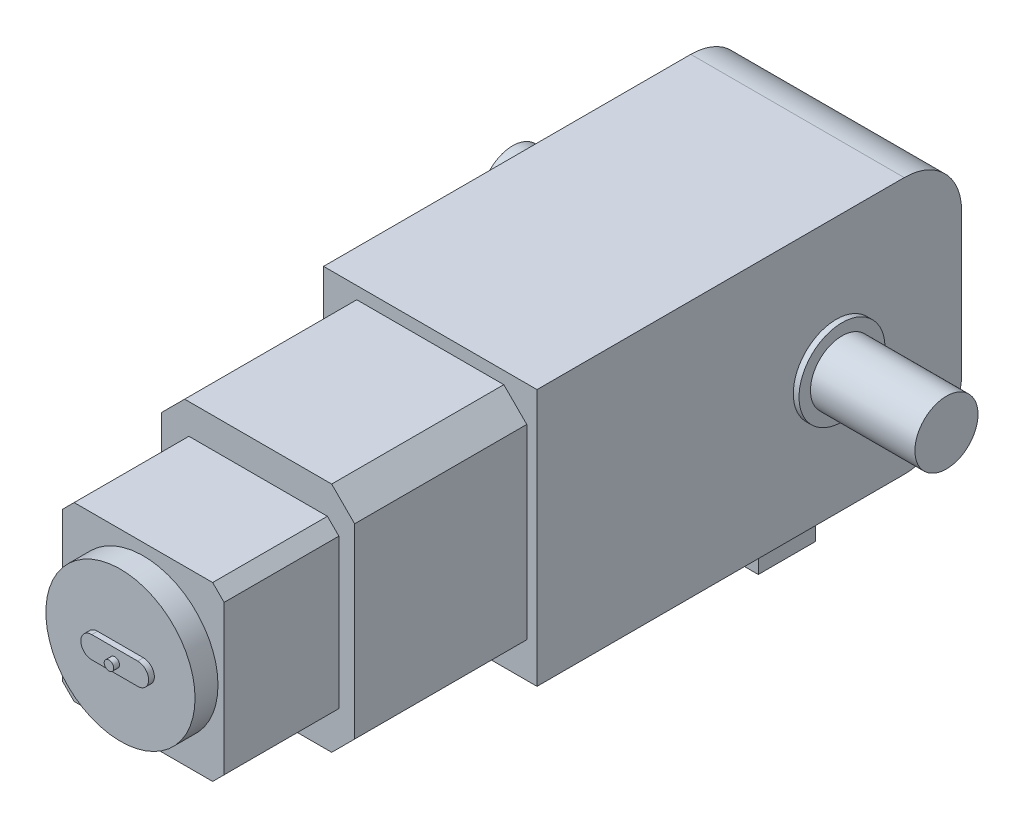
SolidWorks part; units mm, degrees
ref_plane "Front Plane" through (0, 0, 0) normal (0, 0, 1) x (1, 0, 0)
ref_plane "Top Plane" through (0, 0, 0) normal (0, 1, 0) x (1, 0, 0)
ref_plane "Right Plane" through (0, 0, 0) normal (1, 0, 0) x (0, 0, -1)
sketch "Sketch2" plane through (0, 0, 0) normal (1, 0, 0) x (0, 0, -1)
  line L1 (0, 0) -> (32, 0)
  line L2 (0, 0) -> (0, -22.4)
  line L3 (0, -22.4) -> (32, -22.4)
  line L4 (37, -5) -> (37, -17.4)
  arc A0 (32, -22.4) -> (37, -17.4) centre (32, -17.4) ccw
  arc A1 (37, -5) -> (32, 0) centre (32, -5) ccw
  dimension "D1" = 5
extrude "Boss-Extrude2" add sketch "Sketch2" against normal blind 18.6
ref_plane "Plane1" through (-9.3, 0, 0) normal (1, 0, 0) x (0, 0, -1)
sketch "Sketch3" plane through (-9.3, 0, 0) normal (1, 0, 0) x (0, 0, -1)
  line L0 (39, -11.9875) -> (39, -10.9875)
  line L1 (38.5, -10.4875) -> (37, -10.4875)
  line L2 (37, -17.4) -> (37, -5) construction
  line L3 (38.5, -12.4875) -> (37, -12.4875)
  line L4 (37, -17.4) -> (37, -12.4875)
  line L5 (37, -10.4875) -> (37, -12.4875)
  line L8 (0, 0) -> (0, -22.4)
  line L9 (0, -22.4) -> (32, -22.4)
  line L10 (37, -17.4) -> (37, -5)
  line L11 (32, 0) -> (0, 0)
  line L12 (0, 0) -> (0, -22.4)
  line L13 (0, -22.4) -> (32, -22.4)
  line L14 (37, -10.4875) -> (37, -5)
  line L15 (32, 0) -> (0, 0)
  arc A0 (39, -11.9875) -> (38.5, -12.4875) centre (38.5, -11.9875) cw
  arc A1 (39, -10.9875) -> (38.5, -10.4875) centre (38.5, -10.9875) ccw
  arc A4 (32, -22.4) -> (37, -17.4) centre (32, -17.4) ccw
  arc A5 (37, -5) -> (32, 0) centre (32, -5) ccw
  arc A6 (32, -22.4) -> (37, -17.4) centre (32, -17.4) ccw
  arc A7 (37, -5) -> (32, 0) centre (32, -5) ccw
  point P3 (39, -11.4875)
  dimension "D1" = 0.5
  dimension "D2" = 0
extrude "Boss-Extrude3" add sketch "Sketch3" along normal blind 1 and the other way blind 1 contours L0 A1 L1 L5 L3 A0
sketch "Sketch4" plane through (-8.3, 0, 0) normal (1, 0, 0) x (0, 0, -1)
  circle A0 centre (37.8414, -11.4831) radius 0.75
  dimension "2.8" = 1.5
extrude "Cut-Extrude1" cut sketch "Sketch4" against normal through all
sketch "Sketch5" plane through (0, 0, 0) normal (0, 0, 1) x (1, 0, 0)
  line L0 (-17.7069, -3.0755) -> (-15.7069, -1.0755)
  line L1 (0, -22.4) -> (0, 0)
  line L2 (-2.8931, -1.0755) -> (-0.8931, -3.0755)
  line L3 (-17.7069, -19.3245) -> (-15.7069, -21.3245)
  line L4 (-15.7069, -1.0755) -> (-2.8931, -1.0755)
  line L5 (-17.7069, -3.0755) -> (-17.7069, -19.3245)
  line L6 (-15.7069, -21.3245) -> (-2.8931, -21.3245)
  line L7 (-0.8931, -3.0755) -> (-0.8931, -19.3245)
  line L8 (-2.8931, -21.3245) -> (-0.8931, -19.3245)
  point P4 (-9.3, -11.2)
  point P9 (-0.8931, -21.3245)
  point P10 (-17.7069, -1.0755)
  point P11 (-17.7069, -21.3245)
  point P12 (-0.8931, -1.0755)
extrude "Boss-Extrude5" add sketch "Sketch5" along normal blind 15 contours L6 L8 L7 L2 L4 L0 L5 L3
sketch "Sketch6" plane through (0, 0, 15) normal (0, 0, 1) x (1, 0, 0)
  line L0 (-9.3, -12.32) -> (-9.3, 12.32) construction
  line L1 (-15.3351, -3.6927) -> (-3.2649, -3.6927)
  line L2 (-16.3351, -4.6927) -> (-16.3351, -17.7073)
  line L3 (-15.3351, -18.7073) -> (-3.2649, -18.7073)
  line L4 (-2.2649, -4.6927) -> (-2.2649, -17.7073)
  line L5 (-16.3351, -4.6927) -> (-15.3351, -3.6927)
  line L6 (-3.2649, -3.6927) -> (-2.2649, -4.6927)
  line L7 (-3.2649, -18.7073) -> (-2.2649, -17.7073)
  line L8 (-16.3351, -17.7073) -> (-15.3351, -18.7073)
  point P0 (-9.3, -11.2)
  point P1 (-2.2649, -18.7073)
  point P2 (-16.3351, -3.6927)
  point P3 (-16.3351, -18.7073)
  point P4 (-2.2649, -3.6927)
extrude "Boss-Extrude6" add sketch "Sketch6" along normal blind 10
sketch "Sketch7" plane through (0, 0, 25) normal (0, 0, 1) x (1, 0, 0)
  line L0 (-9.3, -12.32) -> (-9.3, 12.32) construction
  circle A0 centre (-9.3, -11.2) radius 6.5
  dimension "D1" = 13
extrude "Boss-Extrude7" add sketch "Sketch7" along normal blind 2
sketch "Sketch8" plane through (0, 0, 27) normal (0, 0, 1) x (1, 0, 0)
  line L0 (-11.3, -10.3878) -> (-7.3, -10.3878)
  line L2 (-11.3, -12.2954) -> (-7.3, -12.2954)
  arc A0 (-11.3, -10.3878) -> (-11.3, -12.2954) centre (-11.3, -11.3416) ccw
  arc A1 (-7.3, -10.3878) -> (-7.3, -12.2954) centre (-7.3, -11.3416) cw
  point P3 (-9.3, -10.3878)
  point P6 (-9.3, -12.2954)
extrude "Boss-Extrude8" add sketch "Sketch8" along normal blind 0.5
sketch "Sketch9" plane through (0, 0, 27.5) normal (0, 0, 1) x (1, 0, 0)
  line L0 (-9.3, -12.32) -> (-9.3, 12.32) construction
  circle A0 centre (-9.3, -11.4732) radius 0.4148
extrude "Boss-Extrude9" add sketch "Sketch9" along normal blind 0.5
sketch "Sketch11" plane through (0, 0, 0) normal (1, 0, 0) x (0, 0, -1)
  circle A1 centre (26.079, -11.4831) radius 3.746
extrude "Boss-Extrude10" add sketch "Sketch11" along normal blind 0.5
sketch "Sketch12" plane through (0.5, 0, 0) normal (1, 0, 0) x (0, 0, -1)
  circle A0 centre (26.079, -11.4831) radius 2.75
  dimension "D1" = 5.5
sketch "Sketch13" plane through (-18.6, 0, 0) normal (-1, 0, 0) x (0, 0, 1)
  circle A0 centre (-26.079, -11.4831) radius 3.8189
extrude "Boss-Extrude11" add sketch "Sketch13" along normal blind 0.5
sketch "Sketch14" plane through (-19.1, 0, 0) normal (-1, 0, 0) x (0, 0, 1)
  circle A0 centre (-26.079, -11.4831) radius 2.75
  dimension "D1" = 5.5
extrude "Boss-Extrude12" add sketch "Sketch14" along normal blind 9.1
extrude "Boss-Extrude13" add sketch "Sketch12" along normal blind 9.1
sketch "Sketch15" plane through (0, -22.4, 0) normal (0, -1, 0) x (1, 0, 0)
  line L1 (-7.8, -28.0828) -> (-7.8, -23.0828)
  line L2 (-7.8, -23.0828) -> (-3.8, -23.0828)
  line L3 (-7.8, -28.0828) -> (-3.8, -28.0828)
  line L4 (-3.8, -23.0828) -> (-3.8, -28.0828)
  line L5 (-10.8, -23.0828) -> (-10.8, -28.0828)
  line L6 (-10.8, -23.0828) -> (-14.8, -23.0828)
  line L7 (-10.8, -28.0828) -> (-14.8, -28.0828)
  line L8 (-14.8, -23.0828) -> (-14.8, -28.0828)
  point P5 (-9.3, -26.079)
extrude "Boss-Extrude14" add sketch "Sketch15" along normal blind 5
